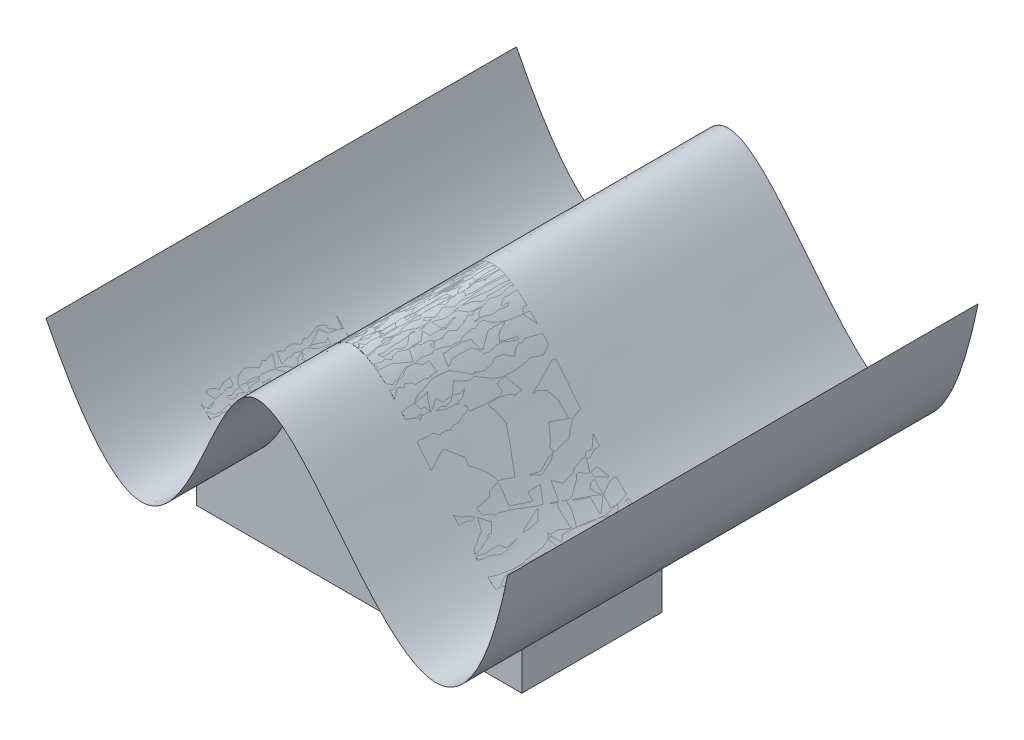
SolidWorks part; units mm, degrees
ref_plane "前视基准面" through (0, 0, 0) normal (0, 0, 1) x (1, 0, 0)
ref_plane "上视基准面" through (0, 0, 0) normal (0, 1, 0) x (1, 0, 0)
ref_plane "右视基准面" through (0, 0, 0) normal (1, 0, 0) x (0, 0, -1)
other "Configuration Table"
sketch "草图1" plane through (0, 0, 0) normal (0, 0, 1) x (1, 0, 0)
  line L1 (-58.1026, -49.4062) -> (58.1026, -49.4062)
  line L2 (-58.1026, -49.4062) -> (-58.1026, 49.4062)
  line L3 (-58.1026, 49.4062) -> (58.1026, 49.4062)
  line L4 (58.1026, -49.4062) -> (58.1026, 49.4062)
  line L5 (-58.1026, -49.4062) -> (58.1026, 49.4062) construction
  line L6 (-58.1026, 49.4062) -> (58.1026, -49.4062) construction
  point P0 (0, 0)
extrude "凸台-拉伸1" add sketch "草图1" along normal blind 50
sketch "草图2" plane through (0, 0, 0) normal (0, 0, 1) x (1, 0, 0)
  spline S0 degree 3 poles (-77.8327, 15.5533) (-31.2958, -76.7212) (-15.7873, 142.0675) (64.2621, -94.6051) (87.0052, 18.4778) knots 0 0 0 0 0.440401 1 1 1 1
surface "曲面-拉伸1" sketch "草图2" parameters "D1"=168
other "使用曲面切除4"
ref_plane "基准面1" through (0, 0, 0) normal (0, 0, -1) x (-1, 0, 0)
